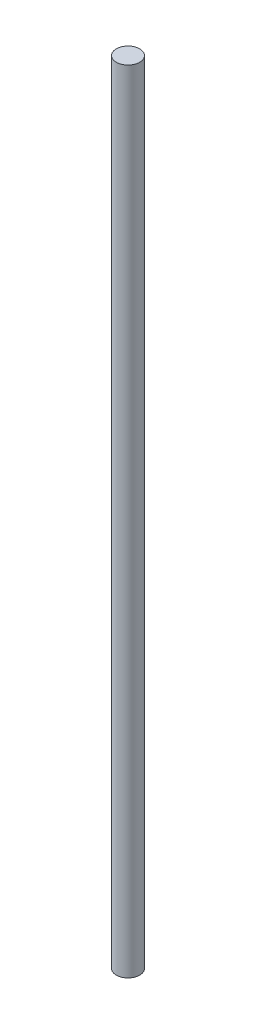
SolidWorks part; units mm, degrees
ref_plane "Front Plane" through (0, 0, 0) normal (0, 0, 1) x (1, 0, 0)
ref_plane "Top Plane" through (0, 0, 0) normal (0, 1, 0) x (1, 0, 0)
ref_plane "Right Plane" through (0, 0, 0) normal (1, 0, 0) x (0, 0, -1)
sketch "Sketch1" plane through (0, 0, 0) normal (0, 1, 0) x (1, 0, 0)
  circle A0 centre (4.781, -5.2529) radius 3.25
  dimension "D1" = 6.5
extrude "Boss-Extrude1" add sketch "Sketch1" along normal blind 220
